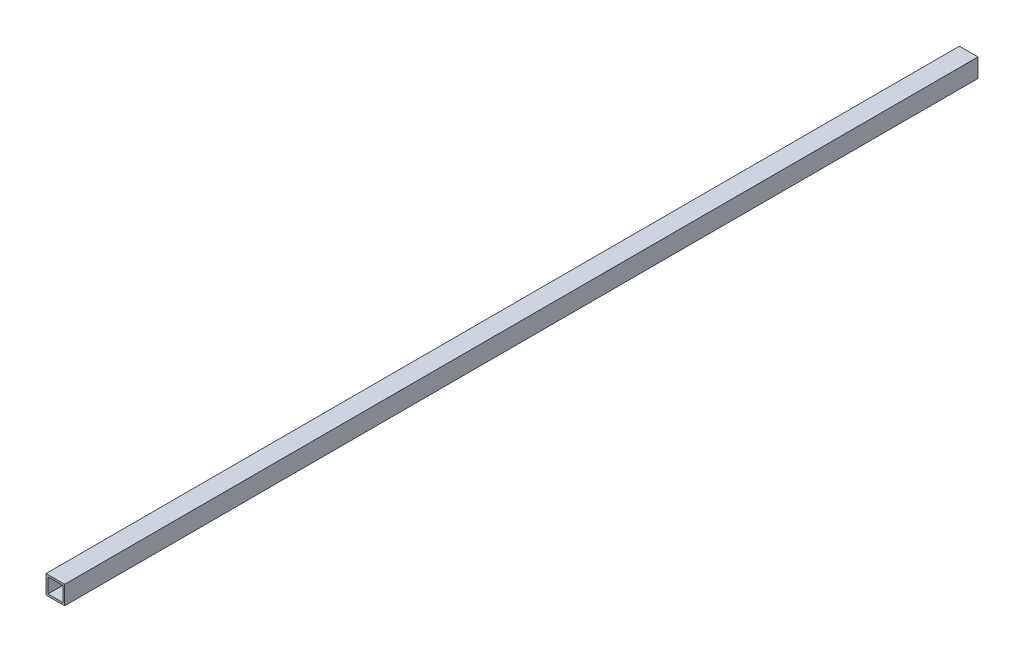
SolidWorks part; units mm, degrees
ref_plane "Płaszczyzna przednia" through (0, 0, 0) normal (0, 0, 1) x (1, 0, 0)
ref_plane "Płaszczyzna górna" through (0, 0, 0) normal (0, 1, 0) x (1, 0, 0)
ref_plane "Płaszczyzna prawa" through (0, 0, 0) normal (1, 0, 0) x (0, 0, -1)
sketch "Szkic1" plane through (0, 0, 0) normal (0, 0, 1) x (1, 0, 0)
  line L1 (-5, -5) -> (5, -5)
  line L2 (-5, -5) -> (-5, 5)
  line L3 (-5, 5) -> (5, 5)
  line L4 (5, -5) -> (5, 5)
  line L5 (-5, -5) -> (5, 5) construction
  line L6 (-5, 5) -> (5, -5) construction
  line L7 (-4, -4) -> (4, -4)
  line L8 (-4, -4) -> (-4, 4)
  line L9 (-4, 4) -> (4, 4)
  line L10 (4, -4) -> (4, 4)
  line L11 (-4, -4) -> (4, 4) construction
  line L12 (-4, 4) -> (4, -4) construction
  point P0 (0, 0)
  point P5 (0, 0)
  dimension "D1" = 10
  dimension "D2" = 8
extrude "Dodanie-wyciągnięcie1" add sketch "Szkic1" along normal blind 490
